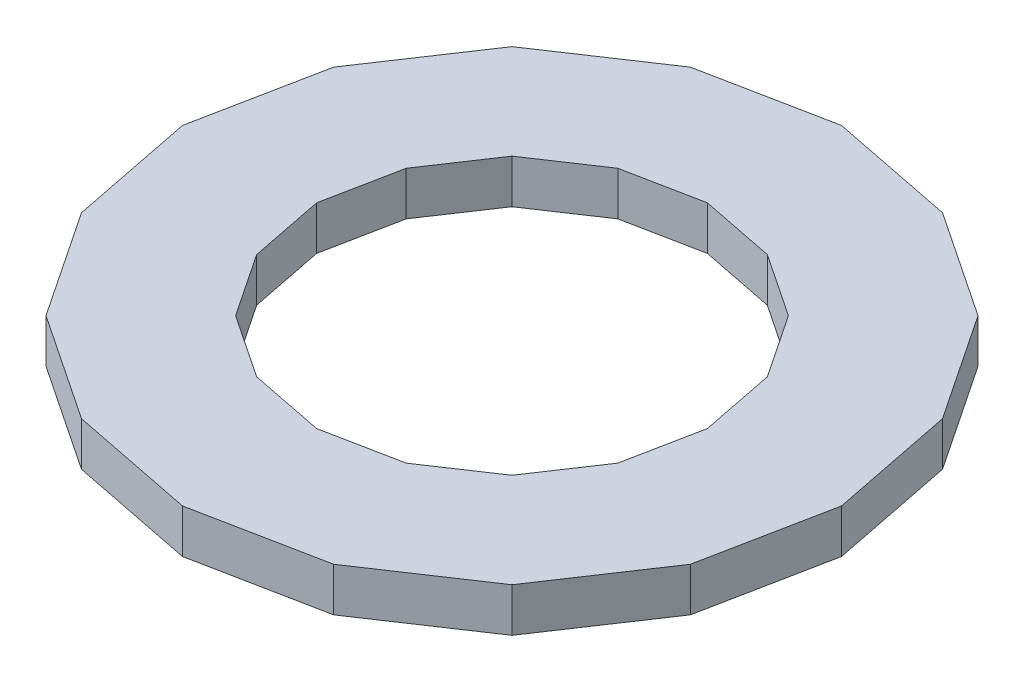
SolidWorks part; units mm, degrees
ref_plane "Front Plane" through (0, 0, 0) normal (0, 0, 1) x (1, 0, 0)
ref_plane "Top Plane" through (0, 0, 0) normal (0, 1, 0) x (1, 0, 0)
ref_plane "Right Plane" through (0, 0, 0) normal (1, 0, 0) x (0, 0, -1)
sketch "Sketch1" plane through (0, 0, 0) normal (0, 1, 0) x (1, 0, 0)
  line L1 (84.9461, 0) -> (78.4799, 32.5075)
  line L2 (78.4799, 32.5075) -> (60.0659, 60.0659)
  line L3 (60.0659, 60.0659) -> (32.5075, 78.4799)
  line L4 (32.5075, 78.4799) -> (0, 84.9461)
  line L5 (0, 84.9461) -> (-32.5075, 78.4799)
  line L6 (-32.5075, 78.4799) -> (-60.0659, 60.0659)
  line L7 (-60.0659, 60.0659) -> (-78.4799, 32.5075)
  line L8 (-78.4799, 32.5075) -> (-84.9461, 0)
  line L9 (-84.9461, 0) -> (-78.4799, -32.5075)
  line L10 (-78.4799, -32.5075) -> (-60.0659, -60.0659)
  line L11 (-60.0659, -60.0659) -> (-32.5075, -78.4799)
  line L12 (-32.5075, -78.4799) -> (0, -84.9461)
  line L13 (0, -84.9461) -> (32.5075, -78.4799)
  line L14 (32.5075, -78.4799) -> (60.0659, -60.0659)
  line L15 (60.0659, -60.0659) -> (78.4799, -32.5075)
  line L16 (78.4799, -32.5075) -> (84.9461, 0)
  line L17 (143.2157, 0) -> (132.3141, 54.8063)
  line L18 (132.3141, 54.8063) -> (101.2688, 101.2688)
  line L19 (101.2688, 101.2688) -> (54.8063, 132.3141)
  line L20 (54.8063, 132.3141) -> (0, 143.2157)
  line L21 (0, 143.2157) -> (-54.8063, 132.3141)
  line L22 (-54.8063, 132.3141) -> (-101.2688, 101.2688)
  line L23 (-101.2688, 101.2688) -> (-132.3141, 54.8063)
  line L24 (-132.3141, 54.8063) -> (-143.2157, 0)
  line L25 (-143.2157, 0) -> (-132.3141, -54.8063)
  line L26 (-132.3141, -54.8063) -> (-101.2688, -101.2688)
  line L27 (-101.2688, -101.2688) -> (-54.8063, -132.3141)
  line L28 (-54.8063, -132.3141) -> (0, -143.2157)
  line L29 (0, -143.2157) -> (54.8063, -132.3141)
  line L30 (54.8063, -132.3141) -> (101.2688, -101.2688)
  line L31 (101.2688, -101.2688) -> (132.3141, -54.8063)
  line L32 (132.3141, -54.8063) -> (143.2157, 0)
  circle A1 centre (0, 0) radius 83.3139 construction
  circle A2 centre (0, 0) radius 140.4639 construction
  dimension "D1" = 57.15
  dimension "D2" = 55.88
extrude "Boss-Extrude1" add sketch "Sketch1" along normal blind 19.05
